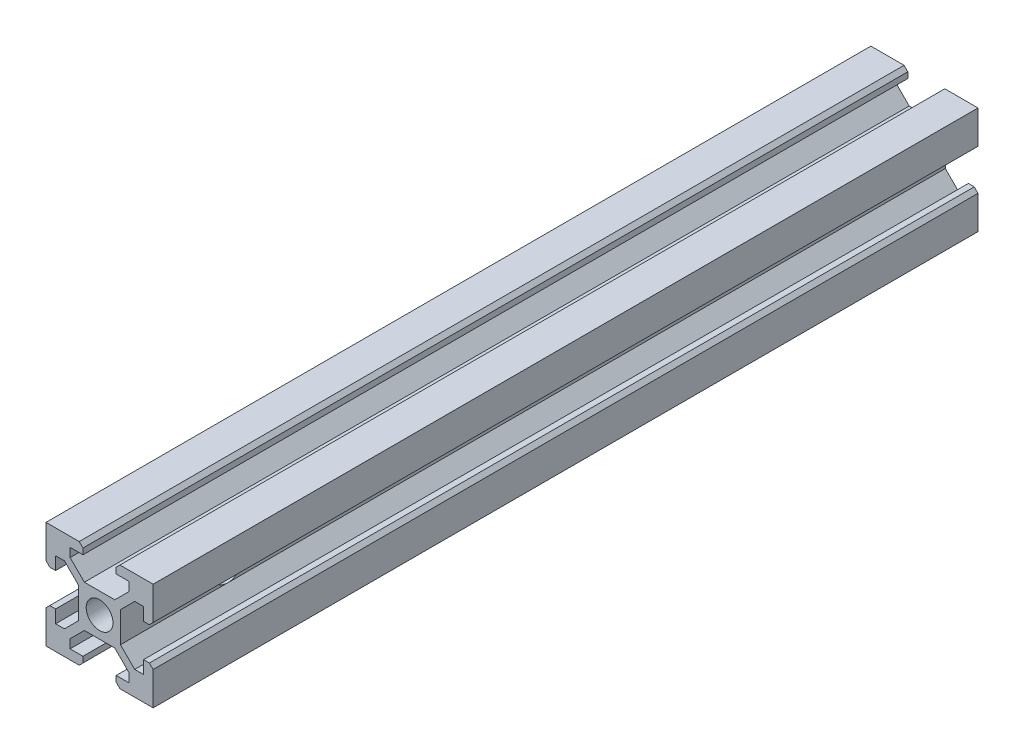
SolidWorks part; units mm, degrees
material "1060 Alloy"
ref_plane "Front Plane" through (0, 0, 0) normal (0, 0, 1) x (1, 0, 0)
ref_plane "Top Plane" through (0, 0, 0) normal (0, 1, 0) x (1, 0, 0)
ref_plane "Right Plane" through (0, 0, 0) normal (1, 0, 0) x (0, 0, -1)
sketch "Sketch1" plane through (0, 0, 0) normal (0, 0, 1) x (1, 0, 0)
  line L0 (3.9, -2.8393) -> (6.5607, -5.5)
  line L1 (-10, 10) -> (10, 10) construction
  line L2 (-10, 10) -> (-10, -10) construction
  line L3 (-10, -10) -> (10, -10) construction
  line L4 (10, 10) -> (10, -10) construction
  line L5 (-10, 10) -> (10, -10) construction
  line L6 (-10, -10) -> (10, 10) construction
  line L7 (-3.9, -3.9) -> (3.9, -3.9) construction
  line L8 (-3.9, -3.9) -> (-3.9, 3.9) construction
  line L9 (-3.9, 3.9) -> (3.9, 3.9) construction
  line L10 (3.9, -3.9) -> (3.9, 3.9) construction
  line L11 (-3.9, -3.9) -> (3.9, 3.9) construction
  line L12 (-3.9, 3.9) -> (3.9, -3.9) construction
  line L13 (-10, 10) -> (-5.5, 10) construction
  line L14 (-10, 10) -> (-10, 5.5) construction
  line L15 (-10, 5.5) -> (-5.5, 5.5) construction
  line L16 (-5.5, 10) -> (-5.5, 5.5) construction
  line L17 (10, 10) -> (5.5, 10) construction
  line L18 (10, 10) -> (10, 5.5) construction
  line L19 (10, 5.5) -> (5.5, 5.5) construction
  line L20 (5.5, 10) -> (5.5, 5.5) construction
  line L21 (-10, -10) -> (-5.5, -10) construction
  line L22 (-10, -10) -> (-10, -5.5) construction
  line L23 (-10, -5.5) -> (-5.5, -5.5) construction
  line L24 (-5.5, -10) -> (-5.5, -5.5) construction
  line L25 (10, -10) -> (5.5, -10) construction
  line L26 (10, -10) -> (10, -5.5) construction
  line L27 (10, -5.5) -> (5.5, -5.5) construction
  line L28 (5.5, -10) -> (5.5, -5.5) construction
  line L29 (2.8393, -3.9) -> (5.5, -6.5607)
  line L30 (-5.5, 6.5607) -> (-2.8393, 3.9)
  line L31 (-6.5607, 5.5) -> (-3.9, 2.8393)
  line L32 (5.5, 6.5607) -> (2.8393, 3.9)
  line L33 (6.5607, 5.5) -> (3.9, 2.8393)
  line L34 (-6.5607, -5.5) -> (-3.9, -2.8393)
  line L35 (-5.5, -6.5607) -> (-2.8393, -3.9)
  line L36 (-2.8393, 3.9) -> (2.8393, 3.9)
  line L37 (-3.9, 2.8393) -> (-3.9, -2.8393)
  line L38 (-2.8393, -3.9) -> (2.8393, -3.9)
  line L39 (3.9, -2.8393) -> (3.9, 2.8393)
  line L40 (5.5, 6.5607) -> (5.5, 8.2007)
  line L41 (5.5, 8.2007) -> (3.1, 8.2007)
  line L42 (3.1, 8.2007) -> (3.1, 9.3)
  line L43 (3.1, 9.3) -> (3.8, 10)
  line L44 (3.8, 10) -> (10, 10)
  line L45 (10, 10) -> (10, 3.8)
  line L46 (10, 3.8) -> (9.3, 3.1)
  line L47 (9.3, 3.1) -> (8.2007, 3.1)
  line L48 (8.2007, 3.1) -> (8.2007, 5.5)
  line L49 (8.2007, 5.5) -> (6.5607, 5.5)
  line L50 (3.1, -8.2007) -> (5.5, -8.2007)
  line L51 (3.1, -9.3) -> (3.1, -8.2007)
  line L52 (3.8, -10) -> (3.1, -9.3)
  line L53 (10, -10) -> (3.8, -10)
  line L54 (10, -3.8) -> (10, -10)
  line L55 (9.3, -3.1) -> (10, -3.8)
  line L56 (8.2007, -3.1) -> (9.3, -3.1)
  line L57 (8.2007, -5.5) -> (8.2007, -3.1)
  line L58 (6.5607, -5.5) -> (8.2007, -5.5)
  line L59 (5.5, -8.2007) -> (5.5, -6.5607)
  line L60 (-8.2007, -3.1) -> (-8.2007, -5.5)
  line L61 (-9.3, -3.1) -> (-8.2007, -3.1)
  line L62 (-10, -3.8) -> (-9.3, -3.1)
  line L63 (-10, -10) -> (-10, -3.8)
  line L64 (-3.8, -10) -> (-10, -10)
  line L65 (-3.1, -9.3) -> (-3.8, -10)
  line L66 (-3.1, -8.2007) -> (-3.1, -9.3)
  line L67 (-5.5, -8.2007) -> (-3.1, -8.2007)
  line L68 (-5.5, -6.5607) -> (-5.5, -8.2007)
  line L69 (-8.2007, -5.5) -> (-6.5607, -5.5)
  line L70 (-3.1, 8.2007) -> (-5.5, 8.2007)
  line L71 (-3.1, 9.3) -> (-3.1, 8.2007)
  line L72 (-3.8, 10) -> (-3.1, 9.3)
  line L73 (-10, 10) -> (-3.8, 10)
  line L74 (-10, 3.8) -> (-10, 10)
  line L75 (-9.3, 3.1) -> (-10, 3.8)
  line L76 (-8.2007, 3.1) -> (-9.3, 3.1)
  line L77 (-8.2007, 5.5) -> (-8.2007, 3.1)
  line L78 (-6.5607, 5.5) -> (-8.2007, 5.5)
  line L79 (-5.5, 8.2007) -> (-5.5, 6.5607)
  circle A0 centre (0, 0) radius 2.5
  point P83 (0, 0)
  dimension "D1" = 5
  dimension "D2" = 20
  dimension "D3" = 7.8
  dimension "D4" = 4.5
  dimension "D5" = 1.5
  dimension "D6" = 0.75
  dimension "D7" = 1.5
  dimension "D8" = 0.75
  dimension "D9" = 1.5
  dimension "D10" = 0.75
  dimension "D11" = 1.5
  dimension "D12" = 0.75
  dimension "D13" = 1.64
  dimension "D14" = 45
  dimension "D15" = 3.1
  dimension "D16" = 6.2
  dimension "D17" = 6.2
  dimension "D18" = 3.1
  dimension "D19" = 4
extrude "Boss-Extrude1" add sketch "Sketch1" along normal mid plane 154 contours L79 L70 L71 L72 L73 L74 L75 L76 L77 L78 L31 L37 L34 L69 L60 L61 L62 L63 L64 L65 L66 L67 L68 L35 L38 L29 L59 L50 L51 L52 L53 L54 L55 L56 L57 L58 L0 L39 L33 L49 L48 L47 L46 L45 L44 L43 L42 L41 L40 L32 L36
sketch "Sketch2" plane through (3.9, 0, 0) normal (1, 0, 0) x (0, 0, -1)
  line L0 (-77, -2.8393) -> (-77, 2.8393) construction
  circle A0 centre (-57, 0) radius 2.8393
  dimension "D1" = 20
extrude "Cut-Extrude1" cut sketch "Sketch2" against normal through all both and the other way through all
